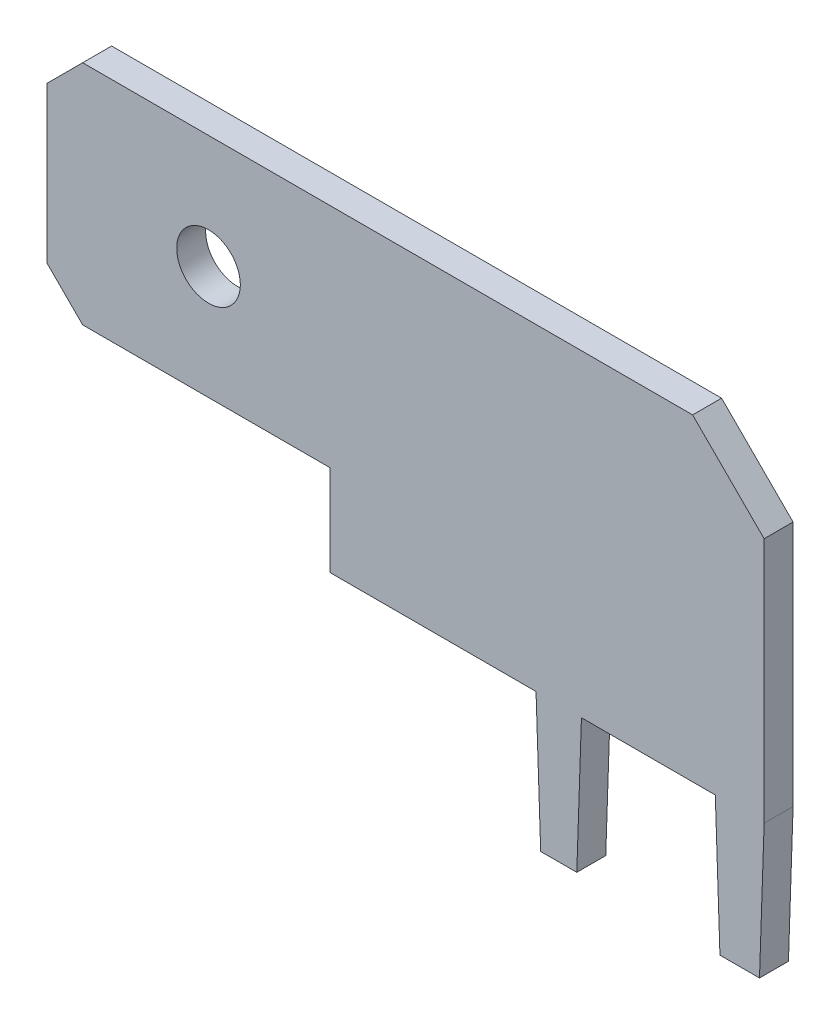
SolidWorks part; units mm, degrees
ref_plane "Plan de face" through (0, 0, 0) normal (0, 0, 1) x (1, 0, 0)
ref_plane "Plan de dessus" through (0, 0, 0) normal (0, 1, 0) x (1, 0, 0)
ref_plane "Plan de droite" through (0, 0, 0) normal (1, 0, 0) x (0, 0, -1)
sketch "Esquisse1" plane through (0, 0, 0) normal (0, 0, 1) x (1, 0, 0)
  line L0 (-13.1041, 11.3619) -> (3.9559, 11.3619)
  line L1 (5.9559, 9.3619) -> (5.9559, 2.4719)
  line L2 (5.9559, 2.4719) -> (5.8261, -1.3426)
  line L3 (4.7201, -1.3426) -> (4.5902, 2.4719)
  line L4 (4.5902, 2.4719) -> (0.8462, 2.4719)
  line L5 (0.8462, 2.4719) -> (0.7162, -1.3381)
  line L6 (0.7162, -1.3381) -> (-0.2938, -1.3381)
  line L7 (-0.2938, -1.3381) -> (-0.4238, 2.4719)
  line L8 (-0.4238, 2.4719) -> (-6.1841, 2.4719)
  line L9 (-6.1841, 2.4719) -> (-6.1841, 5.0119)
  line L10 (-6.1841, 5.0119) -> (-13.1041, 5.0119)
  line L11 (-14.1041, 6.0119) -> (-14.1041, 10.3619)
  line L12 (5.8261, -1.3426) -> (4.7201, -1.3426)
  line L13 (-13.1041, 11.3619) -> (-14.1041, 10.3619)
  line L14 (-14.1041, 6.0119) -> (-13.1041, 5.0119)
  line L15 (3.9559, 11.3619) -> (5.9559, 9.3619)
  point P8 (-14.1041, 11.3619)
  point P18 (-14.1041, 5.0119)
  point P21 (5.9559, 11.3619)
  dimension "D1" = 91.954
  dimension "D2" = 91.954
  dimension "D3" = 91.95
  dimension "D4" = 20.06
  dimension "D5" = 88.05
  dimension "D6" = 8.89
  dimension "D7" = 7.92
  dimension "D8" = 6.35
extrude "Extrusion1" add sketch "Esquisse1" along normal blind 0.81
sketch "Esquisse2" plane through (0, 0, 0.81) normal (0, 0, 1) x (1, 0, 0)
  line L0 (-14.1041, 10.3619) -> (-14.1041, 6.0119) construction
  line L1 (3.9559, 11.3619) -> (-13.1041, 11.3619) construction
  circle A0 centre (-9.5841, 8.1869) radius 0.89
  point P2 (-14.1041, 8.1869)
  dimension "D2" = 3.175
  dimension "D1" = 4.52
extrude "Enlèv. mat.-Extru.1" cut sketch "Esquisse2" against normal blind 0.81
equation "\"D2@Esquisse1\" = \"D1@Esquisse1\""
